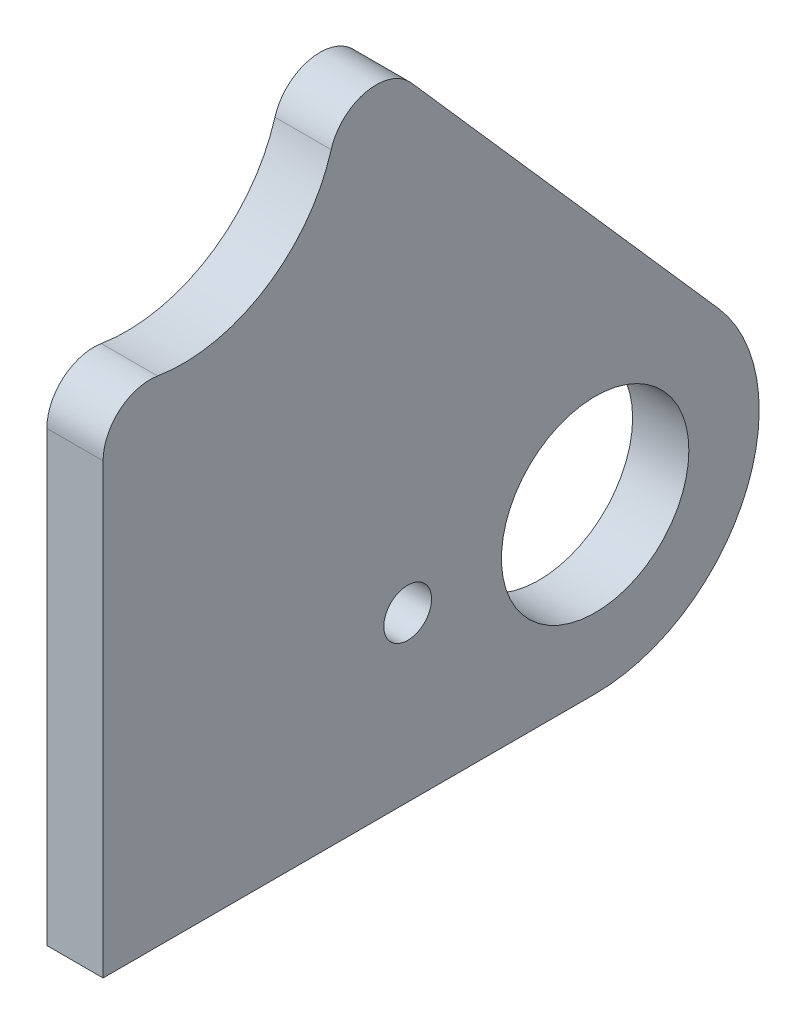
SolidWorks part; units mm, degrees
material "Q355"
ref_plane "前视基准面" through (0, 0, 0) normal (0, 0, 1) x (1, 0, 0)
ref_plane "上视基准面" through (0, 0, 0) normal (0, 1, 0) x (1, 0, 0)
ref_plane "右视基准面" through (0, 0, 0) normal (1, 0, 0) x (0, 0, -1)
sketch "草图1" plane through (0, 0, 0) normal (1, 0, 0) x (0, 0, -1)
  line L0 (0, 0) -> (0, 109.7157)
  line L1 (0, 0) -> (105, 0)
  line L2 (41.7706, 159.804) -> (131.2719, 58.1255)
  circle A0 centre (105, 35) radius 20
  arc A1 (105, 0) -> (131.2719, 58.1255) centre (105, 35) ccw
  arc A3 (0, 109.7157) -> (41.7706, 159.804) centre (17, 138) ccw
  dimension "D1" = 88
  dimension "D2" = 40
  dimension "D3" = 70
  dimension "D4" = 17
  dimension "D6" = 66
  dimension "D5" = 103
extrude "凸台-拉伸1" add sketch "草图1" along normal blind 12
fillet "圆角1" radius 10 2 edges at (6, 159.804, -41.7706) (6, 109.7157, 0)
hole_wizard "M12 螺纹孔1" positions "草图2" profile "草图3" tap size "M12" standard "GB" end condition through all
sketch "草图2" plane through (12, 0, 0) normal (1, 0, 0) x (0, 0, -1)
  line L0 (105, 35) -> (65, 35) construction
  point P0 (65, 35)
  dimension "D1" = 40
sketch "草图3" plane through (12, 35, -65) normal (0, 1, 0) x (0, 0, -1)
  line L0 (0, 0) -> (0, 12)
  line L1 (0, 12) -> (5.1, 12)
  line L2 (5.1, 12) -> (5.1, 0)
  line L5 (5.1, 0) -> (0, 0)
  line L11 (0, -6.35) -> (0, 107.95) construction
  dimension "通孔螺纹孔钻头直径" = 10.2
  dimension "通孔螺纹孔钻头深度" = 12
cosmetic thread "孔螺蚊线1"
